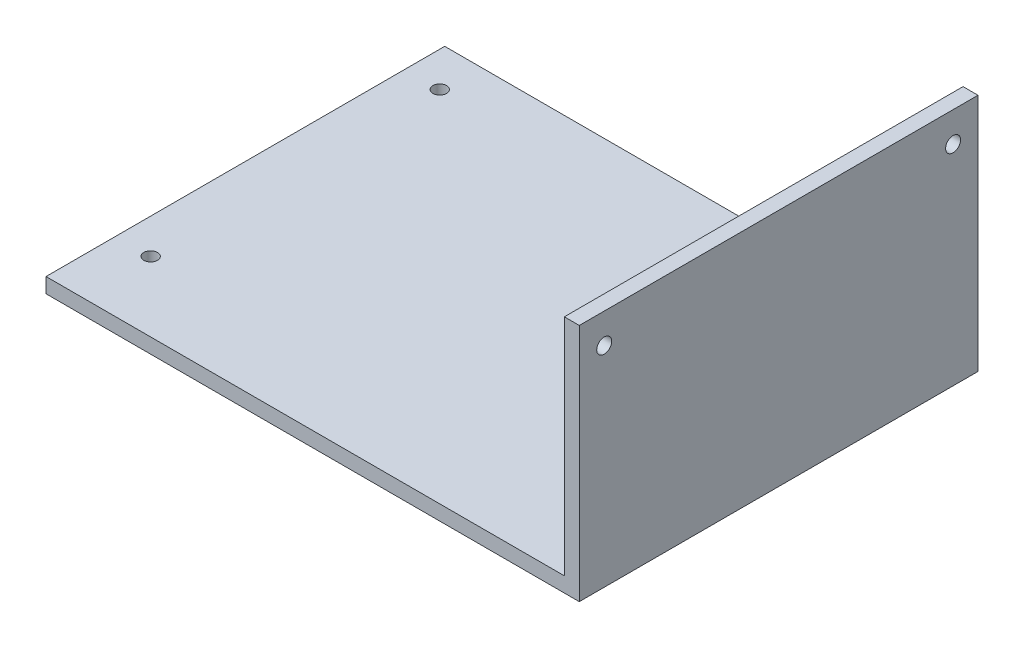
SolidWorks part; units mm, degrees
ref_plane "Front Plane" through (0, 0, 0) normal (0, 0, 1) x (1, 0, 0)
ref_plane "Top Plane" through (0, 0, 0) normal (0, 1, 0) x (1, 0, 0)
ref_plane "Right Plane" through (0, 0, 0) normal (1, 0, 0) x (0, 0, -1)
sketch "Sketch1" plane through (0, 0, 0) normal (0, 1, 0) x (1, 0, 0)
  line L0 (5, 69) -> (5, 11) construction
  line L1 (0, 0) -> (100, 0) construction
  line L2 (0, 0) -> (0, 79) construction
  line L3 (0, 79) -> (100, 79) construction
  line L4 (100, 0) -> (100, 79) construction
  line L5 (5, 69) -> (91, 69) construction
  line L7 (5, 11) -> (91, 11) construction
  line L8 (91, 69) -> (91, 11) construction
  line L13 (-5, -3) -> (105, -3)
  line L14 (105, -3) -> (105, 77)
  line L15 (105, 77) -> (-5, 77)
  line L16 (-5, 77) -> (-5, -3)
  circle A0 centre (5, 11) radius 1.375
  circle A1 centre (5, 69) radius 1.375
  circle A2 centre (91, 69) radius 1.375
  circle A3 centre (91, 11) radius 1.375
  dimension "D5" = 2.75
  dimension "D6" = 100
  dimension "D1" = 86
  dimension "D2" = 58
  dimension "D3" = 10
  dimension "D4" = 5
  dimension "D7" = 79
  dimension "D8" = 8
  dimension "D9" = 5
  dimension "D10" = 5
  dimension "D11" = 3
extrude "Boss-Extrude1" add sketch "Sketch1" along normal blind 3
sketch "Sketch3" plane through (0, 3, 0) normal (0, 1, 0) x (1, 0, 0)
  line L0 (-5, 77) -> (105, 77) construction
  line L1 (-5, -3) -> (-2, -3)
  line L2 (-5, -3) -> (-5, 77)
  line L3 (-5, 77) -> (-2, 77)
  line L4 (-2, -3) -> (-2, 77)
  line L5 (105, -3) -> (-5, -3) construction
  line L6 (105, 77) -> (102, 77)
  line L7 (105, 77) -> (105, -3)
  line L8 (105, -3) -> (102, -3)
  line L9 (102, 77) -> (102, -3)
  dimension "D1" = 3
  dimension "D2" = 3
extrude "Boss-Extrude2" add sketch "Sketch3" along normal blind 45
sketch "Sketch4" plane through (102, 0, 0) normal (-1, 0, 0) x (0, 0, 1)
  line L0 (-72, 42) -> (-2, 42) construction
  line L1 (3, 48) -> (-77, 48) construction
  line L2 (-37, 48) -> (-37, 42) construction
  circle A0 centre (-72, 42) radius 1.5
  circle A1 centre (-2, 42) radius 1.5
  dimension "D1" = 3
  dimension "D2" = 3
  dimension "D3" = 70
  dimension "D4" = 6
extrude "Cut-Extrude1" cut sketch "Sketch4" against normal through all both and the other way through all
sketch "Sketch5" plane through (0, 3, 0) normal (0, 1, 0) x (1, 0, 0)
  line L0 (-2, 77) -> (102, 77) construction
  line L1 (-2, -3) -> (-5, -3)
  line L2 (-2, -3) -> (-2, 77)
  line L3 (-2, 77) -> (-5, 77)
  line L4 (-5, -3) -> (-5, 77)
  line L5 (-2, -3) -> (102, -3) construction
  dimension "D1" = 3
extrude "Cut-Extrude2" cut sketch "Sketch5" against normal through all both and the other way through all
